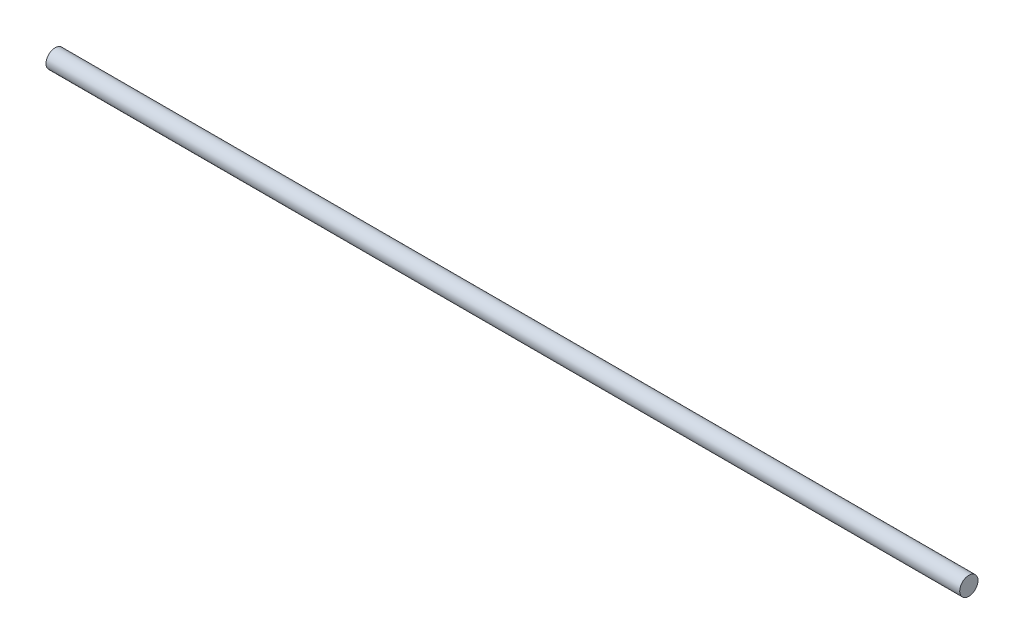
SolidWorks part; units mm, degrees
ref_plane "Plano frontal" through (0, 0, 0) normal (0, 0, 1) x (1, 0, 0)
ref_plane "Plano superior" through (0, 0, 0) normal (0, 1, 0) x (1, 0, 0)
ref_plane "Plano direito" through (0, 0, 0) normal (1, 0, 0) x (0, 0, -1)
sketch "Esboço1" plane through (0, 0, 0) normal (1, 0, 0) x (0, 0, -1)
  circle A0 centre (0, 0) radius 4
  dimension "D1" = 8
extrude "Ressalto-extrusão1" add sketch "Esboço1" along normal blind 400
